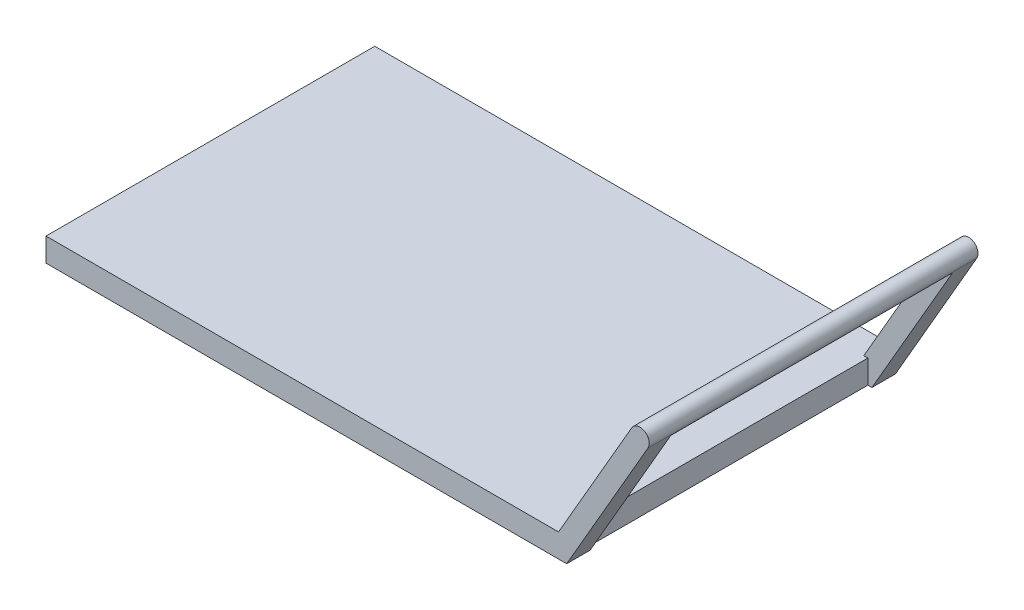
SolidWorks part; units mm, degrees
ref_plane "Front Plane" through (0, 0, 0) normal (0, 0, 1) x (1, 0, 0)
ref_plane "Top Plane" through (0, 0, 0) normal (0, 1, 0) x (1, 0, 0)
ref_plane "Right Plane" through (0, 0, 0) normal (1, 0, 0) x (0, 0, -1)
sketch "Sketch1" plane through (0, 0, 0) normal (0, 1, 0) x (1, 0, 0)
  line L1 (-55, -35) -> (55, -35)
  line L2 (-55, -35) -> (-55, 35)
  line L3 (-55, 35) -> (55, 35)
  line L4 (55, -35) -> (55, 35)
  line L5 (-55, -35) -> (55, 35) construction
  line L6 (-55, 35) -> (55, -35) construction
  point P0 (0, 0)
  dimension "D1" = 110
  dimension "D2" = 70
extrude "Boss-Extrude1" add sketch "Sketch1" along normal blind 5
sketch "Sketch2" plane through (0, 0, 35) normal (0, 0, 1) x (1, 0, 0)
  line L0 (55, 2.5) -> (69.9303, 28.36) construction
  line L1 (55, 5) -> (55, 0) construction
  line L2 (55, 2.5) -> (55, 13.1359) construction
  line L3 (69.7224, 32) -> (73.1865, 30)
  line L4 (54.134, 5) -> (55, 5)
  line L5 (73.1865, 30) -> (55.866, 0)
  line L6 (55.866, 0) -> (55, 0)
  line L7 (69.7224, 32) -> (54.134, 5)
  line L8 (-55, 5) -> (55, 5) construction
  line L9 (55, 5) -> (55, 0)
  dimension "D1" = 30
  dimension "D2" = 2
  dimension "D3" = 2
  dimension "D4" = 30
extrude "Boss-Extrude2" add sketch "Sketch2" against normal blind 5
sketch "Sketch3" plane through (0, 0, -35) normal (0, 0, -1) x (-1, 0, 0)
  line L6 (-54.134, 5) -> (-69.7224, 32)
  line L7 (-69.7224, 32) -> (-73.1865, 30)
  line L8 (-73.1865, 30) -> (-55.866, 0)
  line L9 (-55.866, 0) -> (-55, 0)
  line L10 (-55, 0) -> (-55, 5)
  line L11 (-55, 5) -> (-54.134, 5)
  line L12 (-54.134, 5) -> (-69.7224, 32)
  line L13 (-69.7224, 32) -> (-73.1865, 30)
  line L14 (-73.1865, 30) -> (-55.866, 0)
  line L15 (-55.866, 0) -> (-55, 0)
  line L16 (-55, 0) -> (-55, 5)
  line L17 (-55, 5) -> (-54.134, 5)
  dimension "D1" = 0
extrude "Boss-Extrude3" add sketch "Sketch3" against normal blind 5
sketch "Sketch4" plane through (0, 0, 35) normal (0, 0, 1) x (1, 0, 0)
  line L0 (73.1865, 30) -> (69.7224, 32) construction
  circle A0 centre (71.4545, 31) radius 2
extrude "Boss-Extrude4" add sketch "Sketch4" against normal up to surface (70 mm away)
